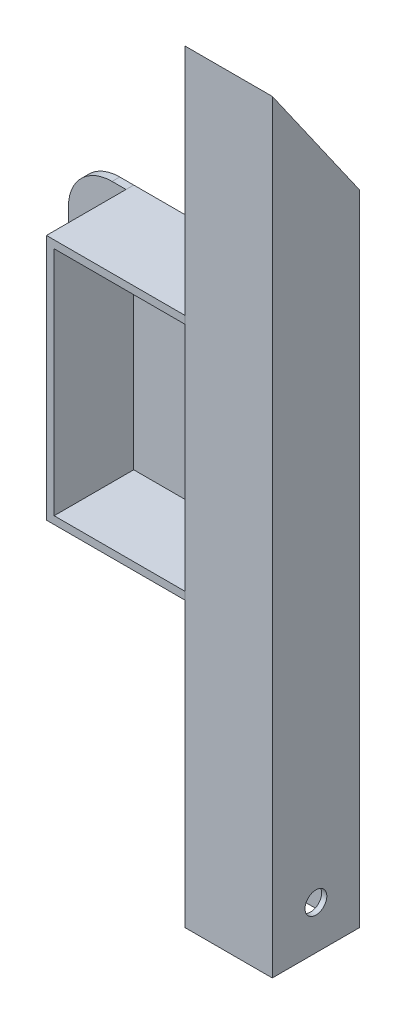
SolidWorks part; units mm, degrees
ref_plane "Front Plane" through (0, 0, 0) normal (0, 0, 1) x (1, 0, 0)
ref_plane "Top Plane" through (0, 0, 0) normal (0, 1, 0) x (1, 0, 0)
ref_plane "Right Plane" through (0, 0, 0) normal (1, 0, 0) x (0, 0, -1)
sketch "Sketch2" plane through (0, 0, 0) normal (0, 1, 0) x (1, 0, 0)
  line L1 (0, 0) -> (25.4, 0)
  line L2 (0, 0) -> (0, 25.4)
  line L3 (0, 25.4) -> (25.4, 25.4)
  line L4 (25.4, 0) -> (25.4, 25.4)
  dimension "D1" = 25.4
  dimension "D2" = 25.4
extrude "Boss-Extrude1" add sketch "Sketch2" along normal blind 222.25
sketch "Sketch3" plane through (25.4, 0, 0) normal (1, 0, 0) x (0, 0, -1)
  line L0 (0, 222.25) -> (25.4, 222.25)
  line L1 (25.4, 222.25) -> (25.4, 185.975)
  line L2 (25.4, 222.25) -> (25.4, 0) construction
  line L3 (25.4, 185.975) -> (0, 222.25)
  dimension "D1" = 145
extrude "Cut-Extrude1" cut sketch "Sketch3" against normal through all and the other way through all
sketch "Sketch5" plane through (0, 0, -25.4) normal (0, 0, -1) x (-1, 0, 0)
  line L0 (0, 185.975) -> (0, 0) construction
  line L1 (0, 154.3304) -> (40.3352, 154.3304)
  line L2 (0, 154.3304) -> (0, 82.55)
  line L3 (0, 82.55) -> (40.3352, 82.55)
  line L4 (40.3352, 154.3304) -> (40.3352, 82.55)
  line L5 (-25.4, 0) -> (0, 0) construction
  dimension "D1" = 40.3352
  dimension "D2" = 71.7804
  dimension "D3" = 82.55
extrude "Boss-Extrude2" add sketch "Sketch5" against normal up to surface (25.4 mm away) separate body up to face at (12.7, 111.125, 0)
sketch "Sketch6" plane through (0, 0, 0) normal (0, 0, 1) x (1, 0, 0)
  line L0 (0, 82.55) -> (0, 154.3304) construction
  line L1 (0, 152.0952) -> (-38.1, 152.0952)
  line L2 (0, 152.0952) -> (0, 84.7852)
  line L3 (0, 84.7852) -> (-38.1, 84.7852)
  line L4 (-38.1, 152.0952) -> (-38.1, 84.7852)
  line L5 (0, 154.3304) -> (-40.3352, 154.3304) construction
  line L6 (-40.3352, 154.3304) -> (-40.3352, 82.55) construction
  line L7 (-40.3352, 82.55) -> (0, 82.55) construction
  dimension "D1" = 2.2352
  dimension "D2" = 2.2352
  dimension "D3" = 2.2352
extrude "Cut-Extrude2" cut sketch "Sketch6" against normal offset from surface (23.1648 mm away) 2.2352 contours L2 L1 L4 L3 up to face at (-20.1676, 118.4402, -25.4)
sketch "Sketch7" plane through (0, 0, -25.4) normal (0, 0, -1) x (-1, 0, 0)
  line L0 (0, 82.55) -> (40.3352, 82.55) construction
  line L1 (40.3352, 154.3304) -> (44.3992, 154.3304)
  line L2 (40.3352, 154.3304) -> (40.3352, 82.55)
  line L3 (40.3352, 82.55) -> (44.3992, 82.55)
  line L4 (57.0992, 141.6304) -> (57.0992, 95.25)
  circle A0 centre (48.7172, 142.9004) radius 1.1557
  circle A1 centre (48.7172, 130.2004) radius 1.1557
  circle A2 centre (48.7172, 117.5004) radius 1.1557
  circle A3 centre (48.7172, 104.8004) radius 1.1557
  circle A4 centre (48.7172, 92.1004) radius 1.1557
  arc A5 (44.3992, 82.55) -> (57.0992, 95.25) centre (44.3992, 95.25) ccw
  arc A6 (57.0992, 141.6304) -> (44.3992, 154.3304) centre (44.3992, 141.6304) ccw
  point P23 (57.0992, 154.3304)
  point P24 (-35.2236, 114.0019)
  dimension "D2" = 2.3114
  dimension "D4" = 11.43
  dimension "D5" = 12.7
  dimension "D1" = 16.764
  dimension "D3" = 5
extrude "Boss-Extrude3" add sketch "Sketch7" against normal blind 2.2352 separate body
sketch "Sketch8" plane through (25.4, 0, 0) normal (1, 0, 0) x (0, 0, -1)
  line L0 (0, 222.25) -> (0, 0) construction
  line L1 (0, 0) -> (25.4, 0) construction
  circle A0 centre (12.7, 12.7) radius 3.175
  dimension "D1" = 6.35
  dimension "D2" = 12.7
  dimension "D3" = 12.7
extrude "Cut-Extrude3" cut sketch "Sketch8" against normal through all
sketch "Sketch9" plane through (0, 0, 0) normal (0, -1, 0) x (1, 0, 0)
  line L4 (0, 0) -> (0, -25.4)
  line L5 (0, -25.4) -> (25.4, -25.4)
  line L6 (25.4, -25.4) -> (25.4, 0)
  line L7 (25.4, 0) -> (0, 0)
  line L8 (0, 0) -> (0, -25.4)
  line L9 (0, -25.4) -> (25.4, -25.4)
  line L10 (25.4, -25.4) -> (25.4, 0)
  line L11 (25.4, 0) -> (0, 0)
  line L16 (1.524, -1.524) -> (1.524, -23.876)
  line L17 (1.524, -23.876) -> (23.876, -23.876)
  line L18 (23.876, -23.876) -> (23.876, -1.524)
  line L19 (23.876, -1.524) -> (1.524, -1.524)
  line L20 (1.524, -1.524) -> (1.524, -23.876)
  line L21 (1.524, -23.876) -> (23.876, -23.876)
  line L22 (23.876, -23.876) -> (23.876, -1.524)
  line L23 (23.876, -1.524) -> (1.524, -1.524)
  dimension "D1" = 0
  dimension "D2" = 1.524
extrude "Cut-Extrude5" cut sketch "Sketch9" against normal through all contours L20 L21 L22 L23
equation "\"D1@Sketch5\"=1.5 + .088"
equation "\"D2@Sketch5\"=2.65 + 2*.088"
